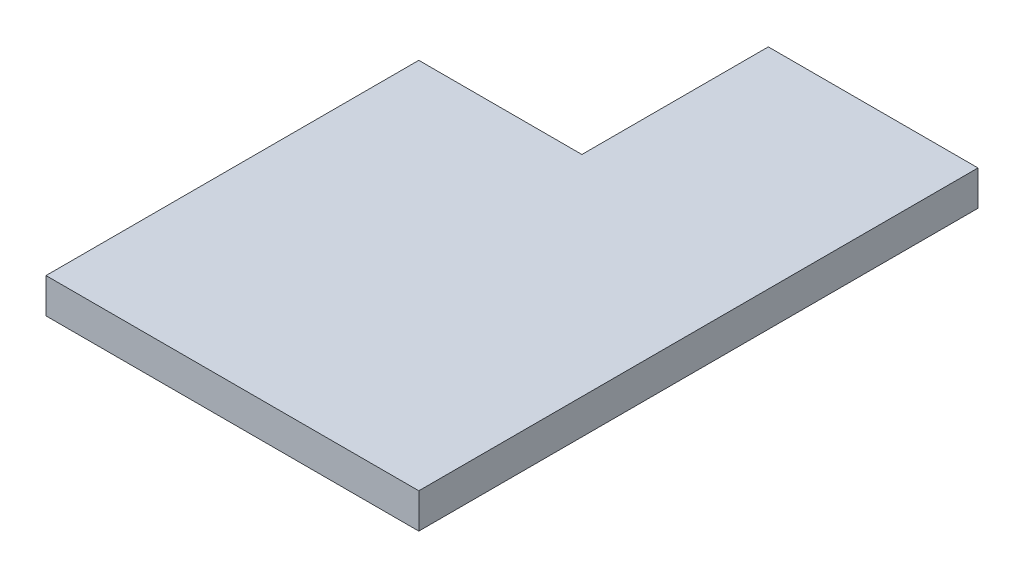
SolidWorks part; units mm, degrees
material "Pine"
ref_plane "Front Plane" through (0, 0, 0) normal (0, 0, 1) x (1, 0, 0)
ref_plane "Top Plane" through (0, 0, 0) normal (0, 1, 0) x (1, 0, 0)
ref_plane "Right Plane" through (0, 0, 0) normal (1, 0, 0) x (0, 0, -1)
sketch "Sketch1" plane through (0, 0, 0) normal (0, 1, 0) x (1, 0, 0)
  line L0 (0, 0) -> (203.2, 0)
  line L1 (203.2, 0) -> (203.2, 304.8)
  line L2 (203.2, 304.8) -> (88.9, 304.8)
  line L3 (88.9, 304.8) -> (88.9, 203.2)
  line L4 (88.9, 203.2) -> (0, 203.2)
  line L5 (0, 203.2) -> (0, 0)
  dimension "D1" = 203.2
  dimension "D2" = 304.8
  dimension "D3" = 101.6
  dimension "D4" = 88.9
extrude "Boss-Extrude1" add sketch "Sketch1" along normal blind 19.05
